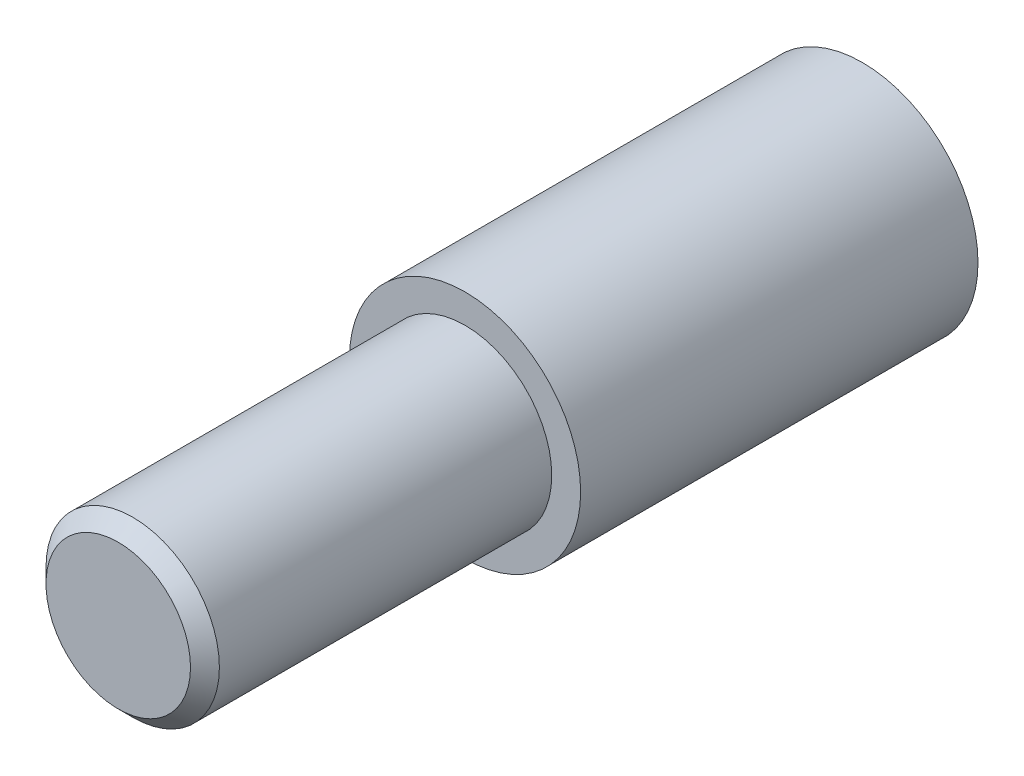
SolidWorks part; units mm, degrees
ref_plane "Alzado" through (0, 0, 0) normal (0, 0, 1) x (1, 0, 0)
ref_plane "Planta" through (0, 0, 0) normal (0, 1, 0) x (1, 0, 0)
ref_plane "Vista lateral" through (0, 0, 0) normal (1, 0, 0) x (0, 0, -1)
sketch "Croquis1" plane through (0, 0, 0) normal (0, 0, 1) x (1, 0, 0)
  circle A0 centre (0, 0) radius 8
  dimension "D1" = 16
extrude "Saliente-Extruir1" add sketch "Croquis1" along normal blind 27.5
sketch "Croquis2" plane through (0, 0, 27.5) normal (0, 0, 1) x (1, 0, 0)
  circle A0 centre (0, 0) radius 6
  dimension "D1" = 12
extrude "Saliente-Extruir2" add sketch "Croquis2" along normal blind 24
chamfer "Chaflán1" distance 1 angle 45 1 edges at (6, 0, 51.5)
